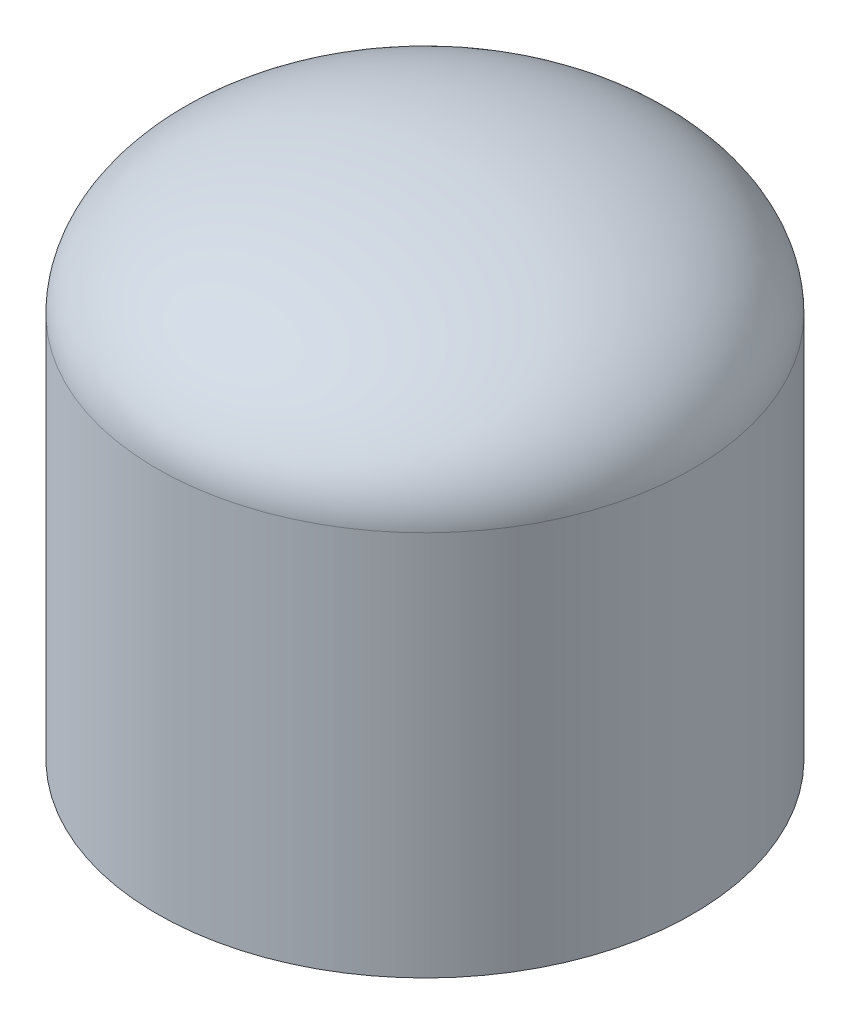
SolidWorks part; units mm, degrees
ref_plane "Front Plane" through (0, 0, 0) normal (0, 0, 1) x (1, 0, 0)
ref_plane "Top Plane" through (0, 0, 0) normal (0, 1, 0) x (1, 0, 0)
ref_plane "Right Plane" through (0, 0, 0) normal (1, 0, 0) x (0, 0, -1)
sketch "Sketch1" plane through (0, 0, 0) normal (0, 0, 1) x (1, 0, 0)
  line L0 (-69.85, 34.925) -> (-69.85, -65.549)
  line L1 (-69.85, -65.549) -> (0, -65.549)
  line L3 (0, 34.925) -> (0, 69.85) construction
  line L4 (-69.85, 34.925) -> (-34.925, 34.925) construction
  line L5 (-34.925, 34.925) -> (0, 34.925) construction
  line L6 (0, 69.85) -> (0, -65.549)
  line L7 (0, 34.925) -> (0, 69.85) construction
  ellipse E0 centre (0, 34.925) end of major axis (69.85, 34.925) minor radius 34.925 (-69.85, 34.925) -> (0, 69.85) cw
  dimension "D1" = 69.85
  dimension "D2" = 135.399
  dimension "D3" = 34.925
revolve "Revolve1" add sketch "Sketch1" angle 360 about L6
